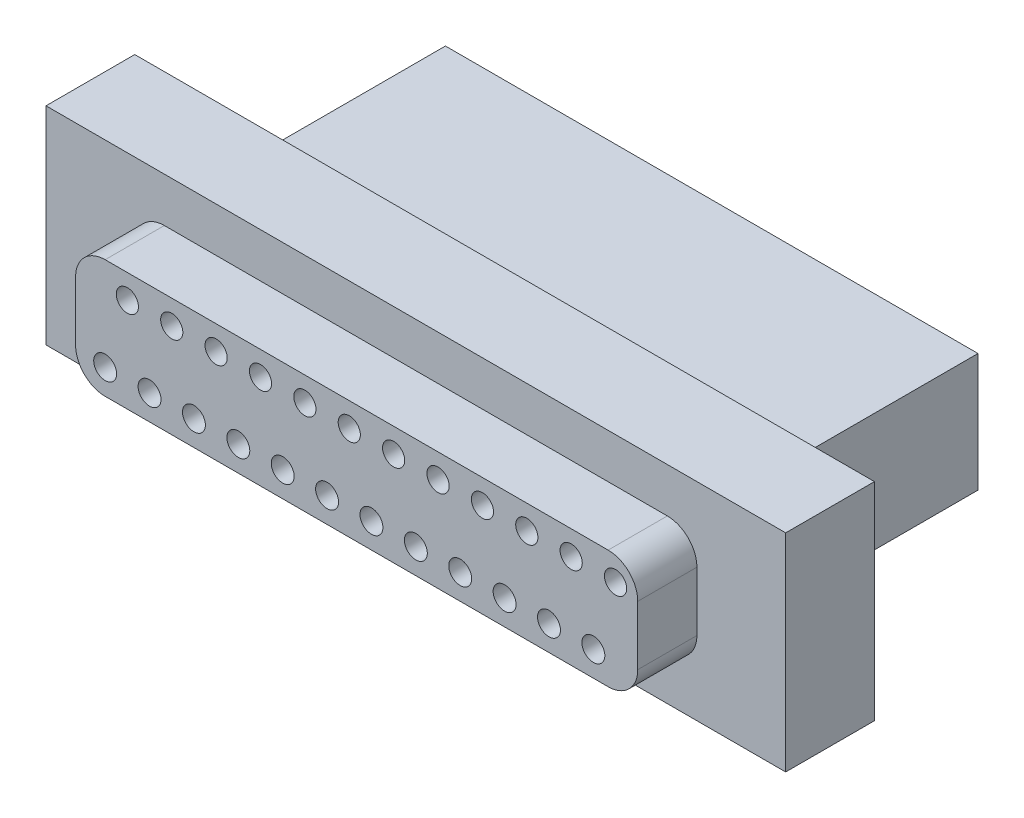
SolidWorks part; units mm, degrees
ref_plane "Front Plane" through (0, 0, 0) normal (0, 0, 1) x (1, 0, 0)
ref_plane "Top Plane" through (0, 0, 0) normal (0, 1, 0) x (1, 0, 0)
ref_plane "Right Plane" through (0, 0, 0) normal (1, 0, 0) x (0, 0, -1)
sketch "Sketch1" plane through (0, 0, 0) normal (0, 1, 0) x (1, 0, 0)
  line L1 (0, 0) -> (50, 0)
  line L2 (0, 0) -> (0, 20)
  line L3 (0, 20) -> (50, 20)
  line L4 (50, 0) -> (50, 20)
  dimension "D1" = 50
  dimension "D2" = 20
extrude "Boss-Extrude1" add sketch "Sketch1" along normal blind 14
sketch "Sketch2" plane through (0, 0, -20) normal (0, 0, -1) x (-1, 0, 0)
  line L0 (-50, 14) -> (0, 14) construction
  line L5 (0, 14) -> (-50, 14)
  line L6 (0, 14) -> (0, 11)
  line L7 (0, 11) -> (-50, 11)
  line L8 (-50, 14) -> (-50, 11)
  line L13 (0, 3) -> (-50, 3)
  line L14 (0, 3) -> (0, 0)
  line L15 (0, 0) -> (-50, 0)
  line L16 (-50, 3) -> (-50, 0)
  line L17 (0, 14) -> (0, 0) construction
  dimension "D1" = 3
  dimension "D2" = 3
extrude "Cut-Extrude1" cut sketch "Sketch2" against normal blind 14
sketch "Sketch3" plane through (0, 0, -20) normal (0, 0, -1) x (-1, 0, 0)
  line L0 (0, 3) -> (-50, 3) construction
  line L1 (0, 11) -> (-7, 11)
  line L2 (0, 11) -> (0, 3)
  line L3 (0, 3) -> (-7, 3)
  line L4 (-7, 11) -> (-7, 3)
  line L5 (-43, 11) -> (-50, 11)
  line L6 (-43, 11) -> (-43, 3)
  line L7 (-43, 3) -> (-50, 3)
  line L8 (-50, 11) -> (-50, 3)
  dimension "D1" = 7
  dimension "D2" = 7
extrude "Cut-Extrude2" cut sketch "Sketch3" against normal blind 14
sketch "Sketch4" plane through (0, 0, 0) normal (0, 0, 1) x (1, 0, 0)
  line L0 (0, 14) -> (0, 0) construction
  line L1 (44, 10.9903) -> (6, 10.9903)
  line L2 (44, 10.9903) -> (44, 2.9903)
  line L3 (44, 2.9903) -> (6, 2.9903)
  line L4 (6, 10.9903) -> (6, 2.9903)
  line L5 (50, 14) -> (50, 0) construction
  line L6 (0, 14) -> (50, 14) construction
  line L7 (0, 0) -> (50, 0) construction
  dimension "D1" = 38
  dimension "D2" = 8
  dimension "D3" = 6
  dimension "D4" = 6
  dimension "D5" = 3.0097
  dimension "D6" = 2.9903
extrude "Boss-Extrude2" add sketch "Sketch4" along normal blind 4
fillet "Fillet2" radius 2 4 edges at (6, 2.9903, 2) (6, 10.9903, 2) (44, 2.9903, 2) (44, 10.9903, 2)
sketch "Sketch5" plane through (0, 0, 4) normal (0, 0, 1) x (1, 0, 0)
  line L0 (44, 4.9903) -> (44, 8.9903) construction
  line L1 (44, 4.9903) -> (44, 8.9903) construction
  line L2 (42, 10.9903) -> (8, 10.9903) construction
  line L3 (8, 2.9903) -> (42, 2.9903) construction
  line L4 (6, 8.9903) -> (6, 4.9903) construction
  circle A0 centre (42.5, 9.3559) radius 0.75
  circle A1 centre (41, 4.6903) radius 0.775
  circle A2 centre (38, 4.6903) radius 0.775
  circle A3 centre (39.5, 9.3559) radius 0.75
  circle A4 centre (35, 4.6903) radius 0.775
  circle A5 centre (36.5, 9.3559) radius 0.75
  circle A6 centre (32, 4.6903) radius 0.775
  circle A7 centre (33.5, 9.3559) radius 0.75
  circle A8 centre (29, 4.6903) radius 0.775
  circle A9 centre (30.5, 9.3559) radius 0.75
  circle A10 centre (26, 4.6903) radius 0.775
  circle A11 centre (27.5, 9.3559) radius 0.75
  circle A12 centre (23, 4.6903) radius 0.775
  circle A13 centre (24.5, 9.3559) radius 0.75
  circle A14 centre (20, 4.6903) radius 0.775
  circle A15 centre (21.5, 9.3559) radius 0.75
  circle A16 centre (17, 4.6903) radius 0.775
  circle A17 centre (18.5, 9.3559) radius 0.75
  circle A18 centre (14, 4.6903) radius 0.775
  circle A19 centre (15.5, 9.3559) radius 0.75
  circle A20 centre (11, 4.6903) radius 0.775
  circle A21 centre (12.5, 9.3559) radius 0.75
  circle A22 centre (8, 4.6903) radius 0.775
  circle A23 centre (9.5, 9.3559) radius 0.75
  dimension "D1" = 1.5
  dimension "D2" = 1.55
  dimension "D3" = 1.5
  dimension "D4" = 3
  dimension "D5" = 1.6344
  dimension "D6" = 1.7
  dimension "D9" = 2
  dimension "D7" = 4.6656
  dimension "D8" = 12
extrude "Cut-Extrude3" cut sketch "Sketch5" against normal blind 10
